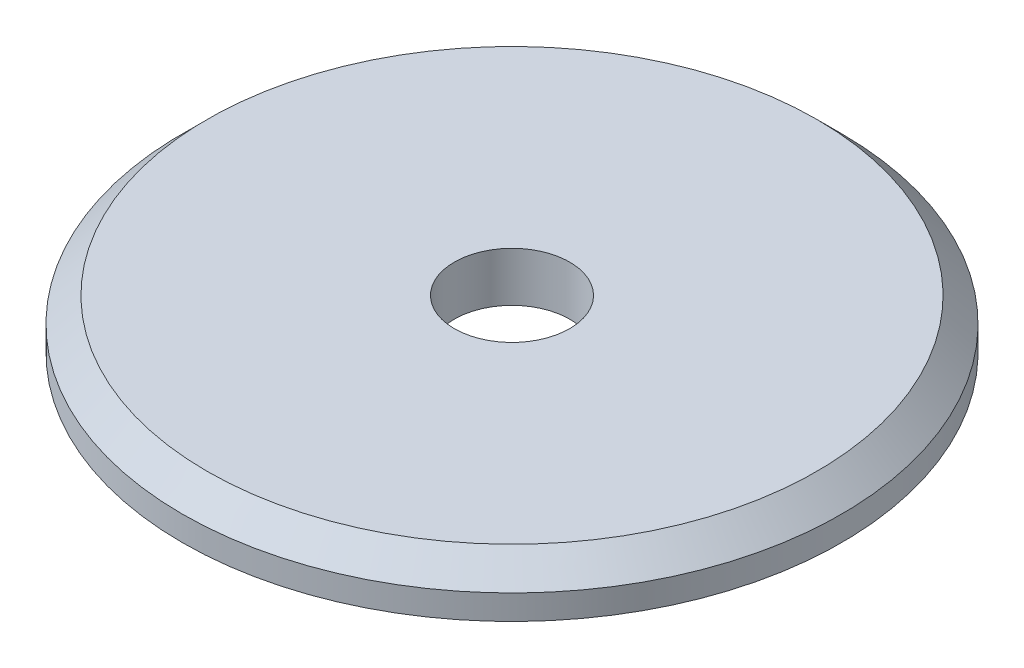
SolidWorks part; units mm, degrees
ref_plane "Front Plane" through (0, 0, 0) normal (0, 0, 1) x (1, 0, 0)
ref_plane "Top Plane" through (0, 0, 0) normal (0, 1, 0) x (1, 0, 0)
ref_plane "Right Plane" through (0, 0, 0) normal (1, 0, 0) x (0, 0, -1)
sketch "Sketch1" plane through (0, 0, 0) normal (0, 1, 0) x (1, 0, 0)
  circle A0 centre (0, 0) radius 3.5
  circle A1 centre (0, 0) radius 20
  dimension "D1" = 7
  dimension "D2" = 40
extrude "Boss-Extrude1" add sketch "Sketch1" along normal blind 3
chamfer "Chamfer1" distance 1.5 angle 45 1 edges at (0, 3, 20)
